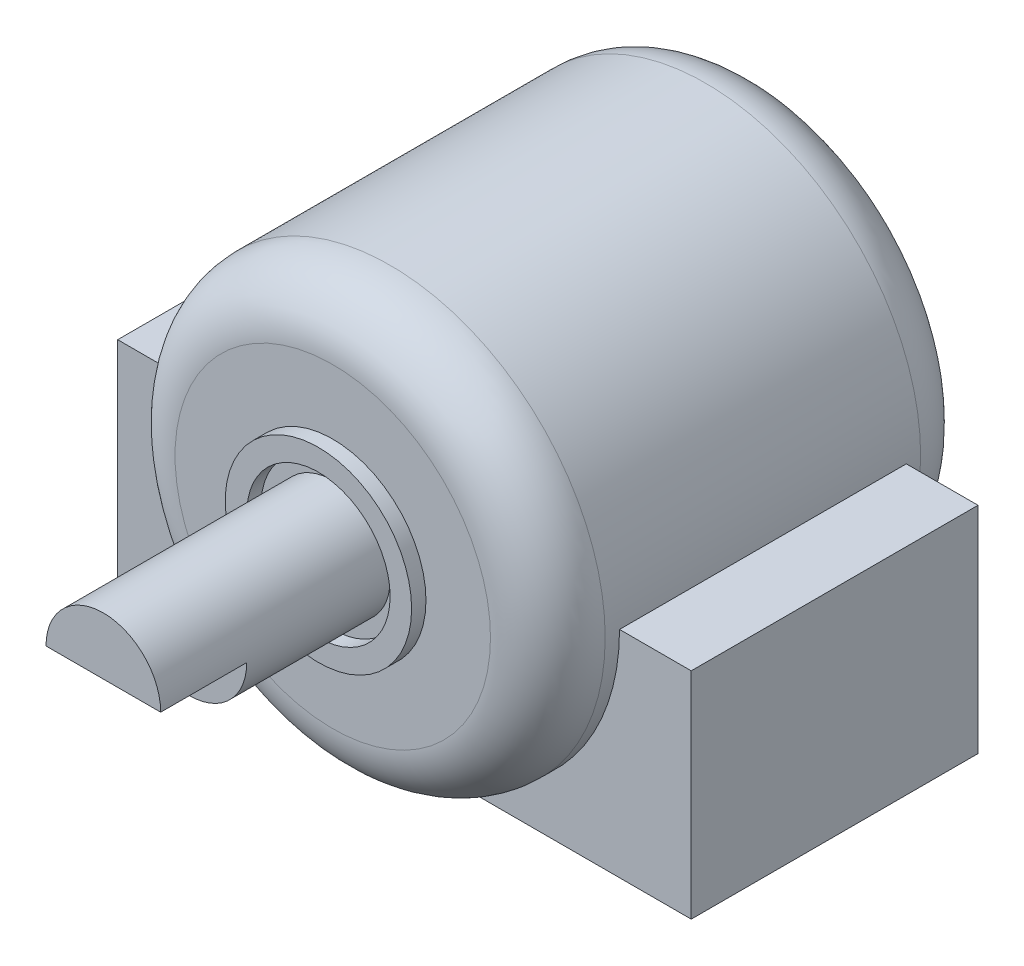
SolidWorks part; units mm, degrees
ref_plane "Front Plane" through (0, 0, 0) normal (0, 0, 1) x (1, 0, 0)
ref_plane "Top Plane" through (0, 0, 0) normal (0, 1, 0) x (1, 0, 0)
ref_plane "Right Plane" through (0, 0, 0) normal (1, 0, 0) x (0, 0, -1)
sketch "Sketch1" plane through (0, 0, 0) normal (0, 0, 1) x (1, 0, 0)
  circle A0 centre (0, 0) radius 7.5
  dimension "D1" = 15
extrude "Boss-Extrude5" add sketch "Sketch1" along normal mid plane 15
sketch "Sketch7" plane through (0, 0, 7.5) normal (0, 0, 1) x (1, 0, 0)
  circle A0 centre (0, 0) radius 2.5
  circle A1 centre (0, 0) radius 3.25
extrude "Boss-Extrude6" add sketch "Sketch7" along normal blind 0.5
sketch "Sketch8" plane through (0, 0, 7.5) normal (0, 0, 1) x (1, 0, 0)
  circle A0 centre (0, 0) radius 2
extrude "Boss-Extrude7" add sketch "Sketch8" along normal blind 8
sketch "Sketch9" plane through (0, 0, 15.5) normal (0, 0, 1) x (1, 0, 0)
  line L0 (-2, 0) -> (2, 0)
  arc A0 (-2, 0) -> (2, 0) centre (0, 0) ccw
extrude "Cut-Extrude2" cut sketch "Sketch9" against normal blind 3
sketch "Sketch10" plane through (0, 0, 0) normal (0, 1, 0) x (1, 0, 0)
  line L1 (-10, 5) -> (10, 5)
  line L2 (-10, 5) -> (-10, -5)
  line L3 (-10, -5) -> (10, -5)
  line L4 (10, 5) -> (10, -5)
  line L5 (-10, 5) -> (10, -5) construction
  line L6 (-10, -5) -> (10, 5) construction
  point P0 (0, 0)
extrude "Boss-Extrude8" add sketch "Sketch10" against normal blind 7.5
fillet "Fillet2" radius 2 2 edges at (7.5, 0, 7.5) (7.5, 0, -7.5)
